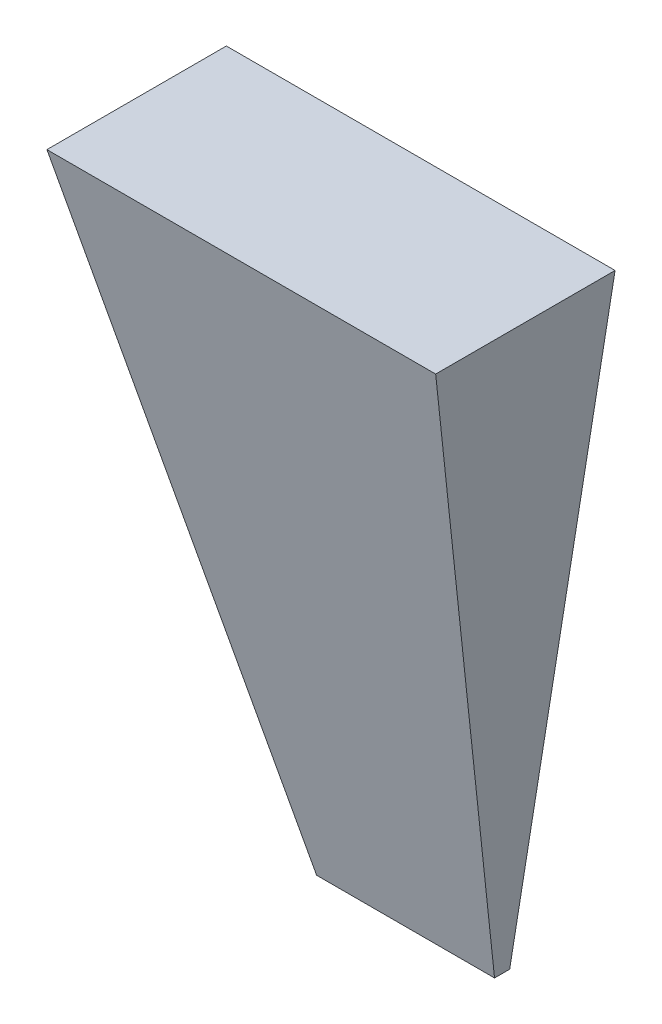
SolidWorks part; units mm, degrees
ref_plane "前视基准面" through (0, 0, 0) normal (0, 0, 1) x (1, 0, 0)
ref_plane "上视基准面" through (0, 0, 0) normal (0, 1, 0) x (1, 0, 0)
ref_plane "右视基准面" through (0, 0, 0) normal (1, 0, 0) x (0, 0, -1)
sketch "草图1" plane through (0, 0, 0) normal (0, 0, 1) x (1, 0, 0)
  line L1 (0, 0) -> (6.5, 0)
  line L2 (0, 0) -> (0, -11)
  line L3 (0, -11) -> (6.5, -11)
  line L4 (6.5, 0) -> (6.5, -11)
  dimension "D1" = 6.5
  dimension "D2" = 11
extrude "凸台-拉伸1" add sketch "草图1" along normal blind 3
sketch "草图2" plane through (6.5, 0, 0) normal (1, 0, 0) x (0, 0, -1)
  line L0 (-3, 0) -> (-0.253, -11)
  line L1 (-3, -11) -> (0, -11) construction
  line L2 (-0.253, -11) -> (-3, -11)
  line L3 (-3, -11) -> (-3, 0)
extrude "切除-拉伸1" cut sketch "草图2" against normal blind 10
sketch "草图3" plane through (0, 0, 0) normal (0, 0, -1) x (-1, 0, 0)
  line L0 (-6.5, 0) -> (-4.7374, -11)
  line L1 (0, -11) -> (-6.5, -11) construction
  line L2 (-4.7374, -11) -> (-6.5, -11)
  line L3 (-6.5, -11) -> (-6.5, 0)
  line L4 (-3.25, 0) -> (-3.25, -10.5482) construction
  line L5 (-6.5, 0) -> (0, 0) construction
  line L6 (-1.7626, -11) -> (0, -11)
  line L7 (0, -11) -> (0, 0)
  line L8 (0, 0) -> (-1.7626, -11)
extrude "切除-拉伸2" cut sketch "草图3" against normal blind 10
